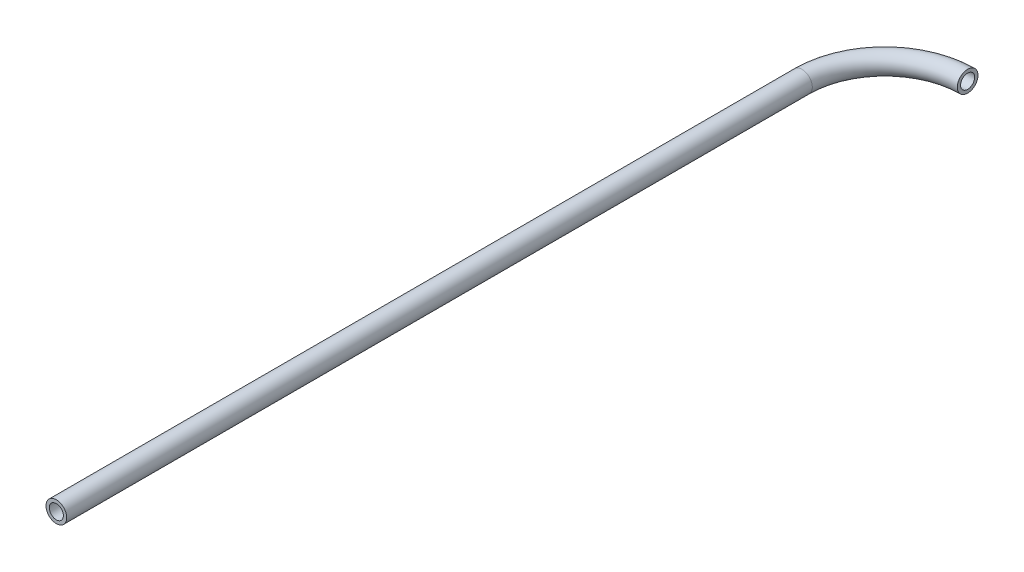
SolidWorks part; units mm, degrees
material "Copper"
ref_plane "Front Plane" through (0, 0, 0) normal (0, 0, 1) x (1, 0, 0)
ref_plane "Top Plane" through (0, 0, 0) normal (0, 1, 0) x (1, 0, 0)
ref_plane "Right Plane" through (0, 0, 0) normal (1, 0, 0) x (0, 0, -1)
sketch "Sketch1" plane through (0, 0, 0) normal (0, 1, 0) x (1, 0, 0)
  line L0 (-51.743, 107.6801) -> (-51.743, -120.9199)
  arc A0 (-26.343, 133.0801) -> (-51.743, 107.6801) centre (-26.343, 107.6801) ccw
  dimension "D1" = 25.4
  dimension "D2" = 228.6
ref_plane "Plane4" through (-51.743, 0, 120.9199) normal (0, 0, 1) x (1, 0, 0)
sketch "Sketch4" plane through (-51.743, 0, 120.9199) normal (0, 0, 1) x (1, 0, 0)
  circle A0 centre (0, 0) radius 3.175
  circle A1 centre (0, 0) radius 2.159
  dimension "D1" = 6.35
  dimension "D2" = 4.318
sweep "Sweep1" add profiles "Sketch4" path "Sketch1"
